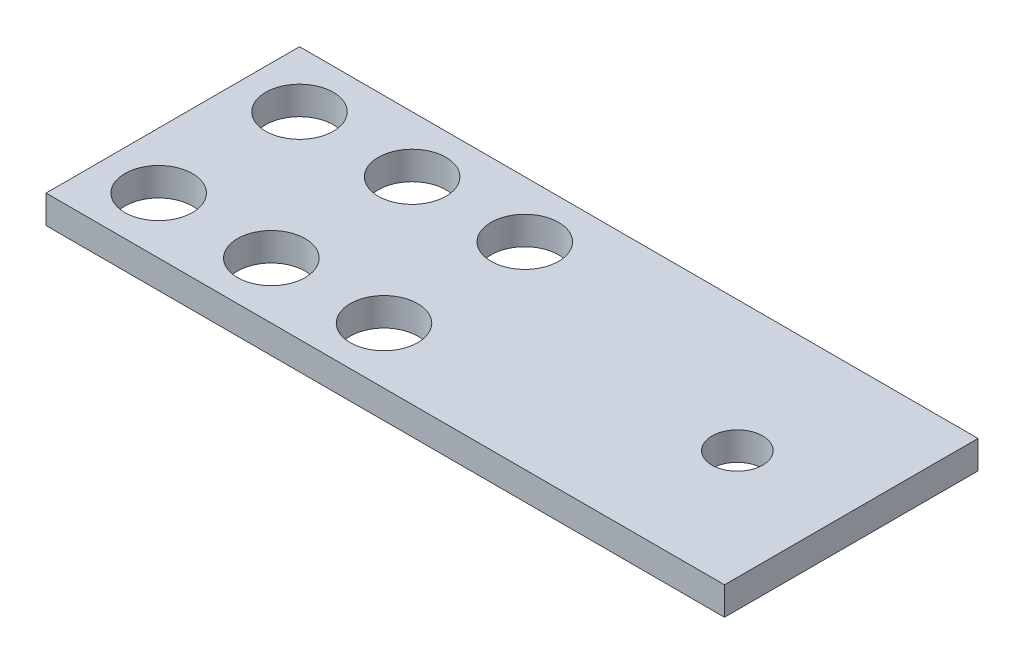
SolidWorks part; units mm, degrees
ref_plane "Front Plane" through (0, 0, 0) normal (0, 0, 1) x (1, 0, 0)
ref_plane "Top Plane" through (0, 0, 0) normal (0, 1, 0) x (1, 0, 0)
ref_plane "Right Plane" through (0, 0, 0) normal (1, 0, 0) x (0, 0, -1)
sketch "Sketch1" plane through (0, 74.2187, 0) normal (0, -1, 0) x (1, 0, 0)
  line L0 (42, 0) -> (42, 350) construction
  line L1 (-78.4511, 332.53) -> (42, 332.53)
  line L2 (-78.4511, 332.53) -> (-78.4511, 287.53)
  line L3 (-78.4511, 287.53) -> (42, 287.53)
  line L4 (42, 332.53) -> (42, 287.53)
  dimension "D1" = 45
extrude "Boss-Extrude1" add sketch "Sketch1" along normal blind 5
hole_wizard "Ø12.0 (12) Diameter Hole1" positions "Sketch5" profile "Sketch3" hole size "Ø12.0" standard "ANSI Metric"
sketch "Sketch5" plane through (0, 74.2187, 0) normal (0, 1, 0) x (1, 0, 0)
  line L0 (-65.9213, -322.53) -> (-9.6104, -322.53) construction
  line L2 (42, -332.53) -> (-78.4511, -332.53) construction
  line L3 (-78.4511, -332.53) -> (-78.4511, -287.53) construction
  line L4 (-81.2659, -297.53) -> (-22.3209, -297.53) construction
  line L6 (-78.4511, -287.53) -> (42, -287.53) construction
  line L7 (-68.4511, -322.53) -> (-68.4511, -297.53) construction
  point P0 (-68.4511, -322.53)
  point P2 (-68.4511, -297.53)
  point P28 (-48.4511, -322.53)
  point P29 (-28.4511, -322.53)
  point P33 (11.5489, -322.53) [skipped]
  point P35 (-8.4511, -322.53) [skipped]
  point P59 (-48.4511, -297.53)
  point P60 (-28.4511, -297.53)
  dimension "D1" = 10
  dimension "D3" = 10
  dimension "D4" = 10
  dimension "D2" = 5
  dimension "D5" = 3
sketch "Sketch3" plane through (-68.4511, 74.2187, 322.53) normal (1, 0, 0) x (0, 0, 1)
  line L0 (0, 0) -> (0, 5)
  line L1 (0, 5) -> (6, 5)
  line L2 (6, 5) -> (6, 0)
  line L5 (6, 0) -> (0, 0)
  line L11 (0, -6.35) -> (0, 107.95) construction
  dimension "Thru Hole Dia." = 12
  dimension "Thru Hole Depth" = 5
hole_wizard "Ø9.0 (9) Diameter Hole1" positions "Sketch8" profile "Sketch7" hole size "Ø9.0" standard "ANSI Metric" end condition through all
sketch "Sketch8" plane through (0, 69.2187, 0) normal (0, -1, 0) x (-1, 0, 0)
  line L0 (-22.5, -332.53) -> (-22.5, -287.53) construction
  line L2 (78.4511, -287.53) -> (-42, -287.53) construction
  line L3 (-42, -332.53) -> (78.4511, -332.53) construction
  point P0 (-22.5, -310.751)
sketch "Sketch7" plane through (22.5, 69.2187, 310.751) normal (1, 0, 0) x (0, 0, -1)
  line L0 (0, 0) -> (0, 5)
  line L1 (0, 5) -> (4.5, 5)
  line L2 (4.5, 5) -> (4.5, 0)
  line L5 (4.5, 0) -> (0, 0)
  line L11 (0, -6.35) -> (0, 107.95) construction
  dimension "Thru Hole Dia." = 9
  dimension "Thru Hole Depth" = 5
